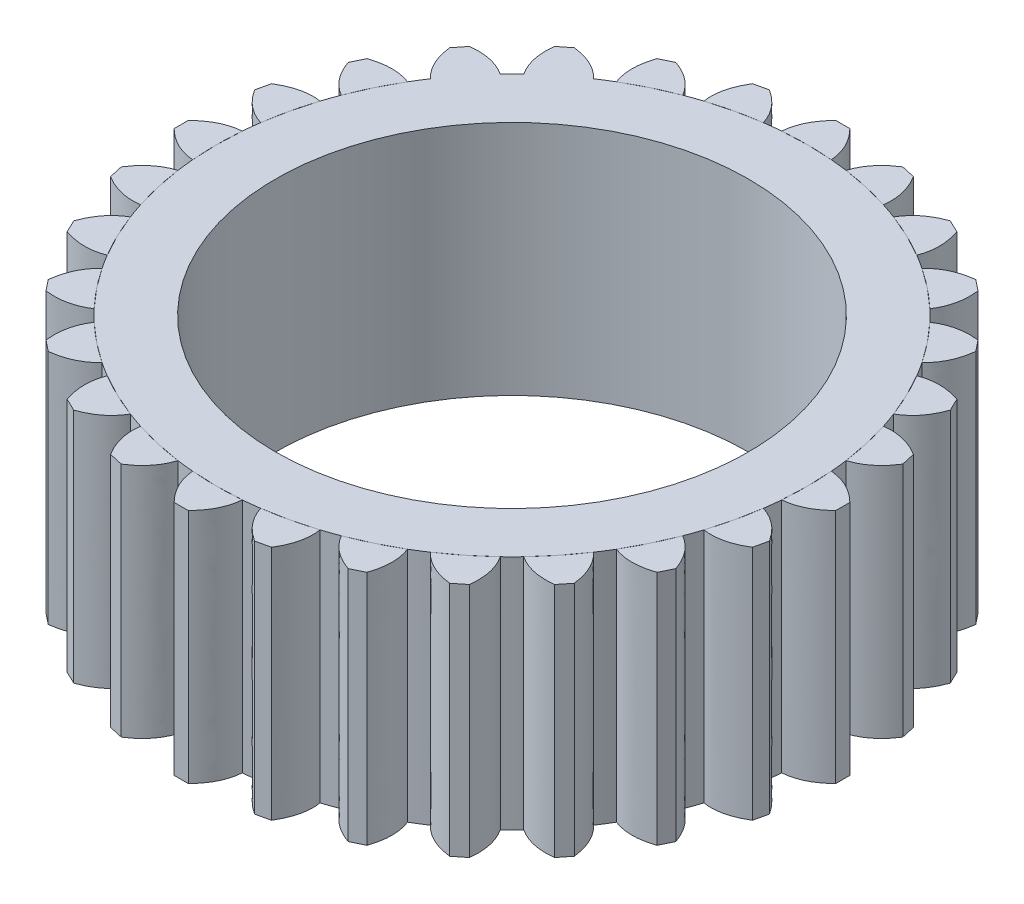
SolidWorks part; units mm, degrees
ref_plane "Front Plane" through (0, 0, 0) normal (0, 0, 1) x (1, 0, 0)
ref_plane "Top Plane" through (0, 0, 0) normal (0, 1, 0) x (1, 0, 0)
ref_plane "Right Plane" through (0, 0, 0) normal (1, 0, 0) x (0, 0, -1)
sketch "Sketch1" plane through (0, 0, 0) normal (0, 1, 0) x (1, 0, 0)
  line L0 (0, 1.4412) -> (0, -1.5503) construction
  line L1 (-0.03, 1.3989) -> (0.03, 1.3989)
  line L2 (0.105, 1.4135) -> (0.105, 1.1584) construction
  line L3 (0.282, 1.3705) -> (0.3405, 1.3572)
  line L4 (0.5799, 1.2734) -> (0.634, 1.2474)
  line L5 (0.8488, 1.1124) -> (0.8957, 1.075)
  line L6 (1.075, 0.8957) -> (1.1124, 0.8488)
  line L7 (1.2474, 0.634) -> (1.2734, 0.5799)
  line L8 (1.3572, 0.3405) -> (1.3705, 0.282)
  line L9 (1.3989, 0.03) -> (1.3989, -0.03)
  line L10 (1.3705, -0.282) -> (1.3572, -0.3405)
  line L11 (1.2734, -0.5799) -> (1.2474, -0.634)
  line L12 (1.1124, -0.8488) -> (1.075, -0.8957)
  line L13 (0.8957, -1.075) -> (0.8488, -1.1124)
  line L14 (0.634, -1.2474) -> (0.5799, -1.2734)
  line L15 (0.3405, -1.3572) -> (0.282, -1.3705)
  line L16 (0.03, -1.3989) -> (-0.03, -1.3989)
  line L17 (-0.282, -1.3705) -> (-0.3405, -1.3572)
  line L18 (-0.5799, -1.2734) -> (-0.634, -1.2474)
  line L19 (-0.8488, -1.1124) -> (-0.8957, -1.075)
  line L20 (-1.075, -0.8957) -> (-1.1124, -0.8488)
  line L21 (-1.2474, -0.634) -> (-1.2734, -0.5799)
  line L22 (-1.3572, -0.3405) -> (-1.3705, -0.282)
  line L23 (-1.3989, -0.03) -> (-1.3989, 0.03)
  line L24 (-1.3705, 0.282) -> (-1.3572, 0.3405)
  line L25 (-1.2734, 0.5799) -> (-1.2474, 0.634)
  line L26 (-1.1124, 0.8488) -> (-1.075, 0.8957)
  line L27 (-0.8957, 1.075) -> (-0.8488, 1.1124)
  line L28 (-0.634, 1.2474) -> (-0.5799, 1.2734)
  line L29 (-0.3405, 1.3572) -> (-0.282, 1.3705)
  circle A0 centre (0, 0) radius 1.25
  spline S0 degree 2 poles (0.03, 1.3989) (0.0985, 1.3294) (0.105, 1.2456) knots 0 0 0 0.82752 0.82752 0.82752
  spline S1 degree 1 poles (0, 1.25) (0.105, 1.2456) knots 0 0 1 1
  spline S2 degree 2 poles (-0.03, 1.3989) (-0.0985, 1.3294) (-0.105, 1.2456) knots 0 0 0 0.82752 0.82752 0.82752
  spline S3 degree 1 poles (0, 1.25) (-0.105, 1.2456) knots 0 0 1 1
  spline S4 degree 1 poles (0.2782, 1.2187) (0.1748, 1.2377) knots 0 0 1 1
  spline S5 degree 1 poles (0.2782, 1.2187) (0.3795, 1.191) knots 0 0 1 1
  spline S6 degree 2 poles (0.3405, 1.3572) (0.3919, 1.2742) (0.3795, 1.191) knots 0 0 0 0.82752 0.82752 0.82752
  spline S7 degree 2 poles (0.282, 1.3705) (0.1998, 1.318) (0.1748, 1.2377) knots 0 0 0 0.82752 0.82752 0.82752
  spline S8 degree 1 poles (0.5424, 1.1262) (0.4458, 1.1678) knots 0 0 1 1
  spline S9 degree 1 poles (0.5424, 1.1262) (0.635, 1.0767) knots 0 0 1 1
  spline S10 degree 2 poles (0.634, 1.2474) (0.6656, 1.155) (0.635, 1.0767) knots 0 0 0 0.82752 0.82752 0.82752
  spline S11 degree 2 poles (0.5799, 1.2734) (0.488, 1.2405) (0.4458, 1.1678) knots 0 0 0 0.82752 0.82752 0.82752
  spline S12 degree 1 poles (0.7794, 0.9773) (0.6945, 1.0393) knots 0 0 1 1
  spline S13 degree 1 poles (0.7794, 0.9773) (0.8587, 0.9084) knots 0 0 1 1
  spline S14 degree 2 poles (0.8957, 1.075) (0.9059, 0.978) (0.8587, 0.9084) knots 0 0 0 0.82752 0.82752 0.82752
  spline S15 degree 2 poles (0.8488, 1.1124) (0.7519, 1.1008) (0.6945, 1.0393) knots 0 0 0 0.82752 0.82752 0.82752
  spline S16 degree 1 poles (0.9773, 0.7794) (0.9084, 0.8587) knots 0 0 1 1
  spline S17 degree 1 poles (0.9773, 0.7794) (1.0393, 0.6945) knots 0 0 1 1
  spline S18 degree 2 poles (1.1124, 0.8488) (1.1008, 0.7519) (1.0393, 0.6945) knots 0 0 0 0.82752 0.82752 0.82752
  spline S19 degree 2 poles (1.075, 0.8957) (0.978, 0.9059) (0.9084, 0.8587) knots 0 0 0 0.82752 0.82752 0.82752
  spline S20 degree 1 poles (1.1262, 0.5424) (1.0767, 0.635) knots 0 0 1 1
  spline S21 degree 1 poles (1.1262, 0.5424) (1.1678, 0.4458) knots 0 0 1 1
  spline S22 degree 2 poles (1.2734, 0.5799) (1.2405, 0.488) (1.1678, 0.4458) knots 0 0 0 0.82752 0.82752 0.82752
  spline S23 degree 2 poles (1.2474, 0.634) (1.155, 0.6656) (1.0767, 0.635) knots 0 0 0 0.82752 0.82752 0.82752
  spline S24 degree 1 poles (1.2187, 0.2782) (1.191, 0.3795) knots 0 0 1 1
  spline S25 degree 1 poles (1.2187, 0.2782) (1.2377, 0.1748) knots 0 0 1 1
  spline S26 degree 2 poles (1.3705, 0.282) (1.318, 0.1998) (1.2377, 0.1748) knots 0 0 0 0.82752 0.82752 0.82752
  spline S27 degree 2 poles (1.3572, 0.3405) (1.2742, 0.3919) (1.191, 0.3795) knots 0 0 0 0.82752 0.82752 0.82752
  spline S28 degree 1 poles (1.25, 0) (1.2456, 0.105) knots 0 0 1 1
  spline S29 degree 1 poles (1.25, 0) (1.2456, -0.105) knots 0 0 1 1
  spline S30 degree 2 poles (1.3989, -0.03) (1.3294, -0.0985) (1.2456, -0.105) knots 0 0 0 0.82752 0.82752 0.82752
  spline S31 degree 2 poles (1.3989, 0.03) (1.3294, 0.0985) (1.2456, 0.105) knots 0 0 0 0.82752 0.82752 0.82752
  spline S32 degree 1 poles (1.2187, -0.2782) (1.2377, -0.1748) knots 0 0 1 1
  spline S33 degree 1 poles (1.2187, -0.2782) (1.191, -0.3795) knots 0 0 1 1
  spline S34 degree 2 poles (1.3572, -0.3405) (1.2742, -0.3919) (1.191, -0.3795) knots 0 0 0 0.82752 0.82752 0.82752
  spline S35 degree 2 poles (1.3705, -0.282) (1.318, -0.1998) (1.2377, -0.1748) knots 0 0 0 0.82752 0.82752 0.82752
  spline S36 degree 1 poles (1.1262, -0.5424) (1.1678, -0.4458) knots 0 0 1 1
  spline S37 degree 1 poles (1.1262, -0.5424) (1.0767, -0.635) knots 0 0 1 1
  spline S38 degree 2 poles (1.2474, -0.634) (1.155, -0.6656) (1.0767, -0.635) knots 0 0 0 0.82752 0.82752 0.82752
  spline S39 degree 2 poles (1.2734, -0.5799) (1.2405, -0.488) (1.1678, -0.4458) knots 0 0 0 0.82752 0.82752 0.82752
  spline S40 degree 1 poles (0.9773, -0.7794) (1.0393, -0.6945) knots 0 0 1 1
  spline S41 degree 1 poles (0.9773, -0.7794) (0.9084, -0.8587) knots 0 0 1 1
  spline S42 degree 2 poles (1.075, -0.8957) (0.978, -0.9059) (0.9084, -0.8587) knots 0 0 0 0.82752 0.82752 0.82752
  spline S43 degree 2 poles (1.1124, -0.8488) (1.1008, -0.7519) (1.0393, -0.6945) knots 0 0 0 0.82752 0.82752 0.82752
  spline S44 degree 1 poles (0.7794, -0.9773) (0.8587, -0.9084) knots 0 0 1 1
  spline S45 degree 1 poles (0.7794, -0.9773) (0.6945, -1.0393) knots 0 0 1 1
  spline S46 degree 2 poles (0.8488, -1.1124) (0.7519, -1.1008) (0.6945, -1.0393) knots 0 0 0 0.82752 0.82752 0.82752
  spline S47 degree 2 poles (0.8957, -1.075) (0.9059, -0.978) (0.8587, -0.9084) knots 0 0 0 0.82752 0.82752 0.82752
  spline S48 degree 1 poles (0.5424, -1.1262) (0.635, -1.0767) knots 0 0 1 1
  spline S49 degree 1 poles (0.5424, -1.1262) (0.4458, -1.1678) knots 0 0 1 1
  spline S50 degree 2 poles (0.5799, -1.2734) (0.488, -1.2405) (0.4458, -1.1678) knots 0 0 0 0.82752 0.82752 0.82752
  spline S51 degree 2 poles (0.634, -1.2474) (0.6656, -1.155) (0.635, -1.0767) knots 0 0 0 0.82752 0.82752 0.82752
  spline S52 degree 1 poles (0.2782, -1.2187) (0.3795, -1.191) knots 0 0 1 1
  spline S53 degree 1 poles (0.2782, -1.2187) (0.1748, -1.2377) knots 0 0 1 1
  spline S54 degree 2 poles (0.282, -1.3705) (0.1998, -1.318) (0.1748, -1.2377) knots 0 0 0 0.82752 0.82752 0.82752
  spline S55 degree 2 poles (0.3405, -1.3572) (0.3919, -1.2742) (0.3795, -1.191) knots 0 0 0 0.82752 0.82752 0.82752
  spline S56 degree 1 poles (0, -1.25) (0.105, -1.2456) knots 0 0 1 1
  spline S57 degree 1 poles (0, -1.25) (-0.105, -1.2456) knots 0 0 1 1
  spline S58 degree 2 poles (-0.03, -1.3989) (-0.0985, -1.3294) (-0.105, -1.2456) knots 0 0 0 0.82752 0.82752 0.82752
  spline S59 degree 2 poles (0.03, -1.3989) (0.0985, -1.3294) (0.105, -1.2456) knots 0 0 0 0.82752 0.82752 0.82752
  spline S60 degree 1 poles (-0.2782, -1.2187) (-0.1748, -1.2377) knots 0 0 1 1
  spline S61 degree 1 poles (-0.2782, -1.2187) (-0.3795, -1.191) knots 0 0 1 1
  spline S62 degree 2 poles (-0.3405, -1.3572) (-0.3919, -1.2742) (-0.3795, -1.191) knots 0 0 0 0.82752 0.82752 0.82752
  spline S63 degree 2 poles (-0.282, -1.3705) (-0.1998, -1.318) (-0.1748, -1.2377) knots 0 0 0 0.82752 0.82752 0.82752
  spline S64 degree 1 poles (-0.5424, -1.1262) (-0.4458, -1.1678) knots 0 0 1 1
  spline S65 degree 1 poles (-0.5424, -1.1262) (-0.635, -1.0767) knots 0 0 1 1
  spline S66 degree 2 poles (-0.634, -1.2474) (-0.6656, -1.155) (-0.635, -1.0767) knots 0 0 0 0.82752 0.82752 0.82752
  spline S67 degree 2 poles (-0.5799, -1.2734) (-0.488, -1.2405) (-0.4458, -1.1678) knots 0 0 0 0.82752 0.82752 0.82752
  spline S68 degree 1 poles (-0.7794, -0.9773) (-0.6945, -1.0393) knots 0 0 1 1
  spline S69 degree 1 poles (-0.7794, -0.9773) (-0.8587, -0.9084) knots 0 0 1 1
  spline S70 degree 2 poles (-0.8957, -1.075) (-0.9059, -0.978) (-0.8587, -0.9084) knots 0 0 0 0.82752 0.82752 0.82752
  spline S71 degree 2 poles (-0.8488, -1.1124) (-0.7519, -1.1008) (-0.6945, -1.0393) knots 0 0 0 0.82752 0.82752 0.82752
  spline S72 degree 1 poles (-0.9773, -0.7794) (-0.9084, -0.8587) knots 0 0 1 1
  spline S73 degree 1 poles (-0.9773, -0.7794) (-1.0393, -0.6945) knots 0 0 1 1
  spline S74 degree 2 poles (-1.1124, -0.8488) (-1.1008, -0.7519) (-1.0393, -0.6945) knots 0 0 0 0.82752 0.82752 0.82752
  spline S75 degree 2 poles (-1.075, -0.8957) (-0.978, -0.9059) (-0.9084, -0.8587) knots 0 0 0 0.82752 0.82752 0.82752
  spline S76 degree 1 poles (-1.1262, -0.5424) (-1.0767, -0.635) knots 0 0 1 1
  spline S77 degree 1 poles (-1.1262, -0.5424) (-1.1678, -0.4458) knots 0 0 1 1
  spline S78 degree 2 poles (-1.2734, -0.5799) (-1.2405, -0.488) (-1.1678, -0.4458) knots 0 0 0 0.82752 0.82752 0.82752
  spline S79 degree 2 poles (-1.2474, -0.634) (-1.155, -0.6656) (-1.0767, -0.635) knots 0 0 0 0.82752 0.82752 0.82752
  spline S80 degree 1 poles (-1.2187, -0.2782) (-1.191, -0.3795) knots 0 0 1 1
  spline S81 degree 1 poles (-1.2187, -0.2782) (-1.2377, -0.1748) knots 0 0 1 1
  spline S82 degree 2 poles (-1.3705, -0.282) (-1.318, -0.1998) (-1.2377, -0.1748) knots 0 0 0 0.82752 0.82752 0.82752
  spline S83 degree 2 poles (-1.3572, -0.3405) (-1.2742, -0.3919) (-1.191, -0.3795) knots 0 0 0 0.82752 0.82752 0.82752
  spline S84 degree 1 poles (-1.25, 0) (-1.2456, -0.105) knots 0 0 1 1
  spline S85 degree 1 poles (-1.25, 0) (-1.2456, 0.105) knots 0 0 1 1
  spline S86 degree 2 poles (-1.3989, 0.03) (-1.3294, 0.0985) (-1.2456, 0.105) knots 0 0 0 0.82752 0.82752 0.82752
  spline S87 degree 2 poles (-1.3989, -0.03) (-1.3294, -0.0985) (-1.2456, -0.105) knots 0 0 0 0.82752 0.82752 0.82752
  spline S88 degree 1 poles (-1.2187, 0.2782) (-1.2377, 0.1748) knots 0 0 1 1
  spline S89 degree 1 poles (-1.2187, 0.2782) (-1.191, 0.3795) knots 0 0 1 1
  spline S90 degree 2 poles (-1.3572, 0.3405) (-1.2742, 0.3919) (-1.191, 0.3795) knots 0 0 0 0.82752 0.82752 0.82752
  spline S91 degree 2 poles (-1.3705, 0.282) (-1.318, 0.1998) (-1.2377, 0.1748) knots 0 0 0 0.82752 0.82752 0.82752
  spline S92 degree 1 poles (-1.1262, 0.5424) (-1.1678, 0.4458) knots 0 0 1 1
  spline S93 degree 1 poles (-1.1262, 0.5424) (-1.0767, 0.635) knots 0 0 1 1
  spline S94 degree 2 poles (-1.2474, 0.634) (-1.155, 0.6656) (-1.0767, 0.635) knots 0 0 0 0.82752 0.82752 0.82752
  spline S95 degree 2 poles (-1.2734, 0.5799) (-1.2405, 0.488) (-1.1678, 0.4458) knots 0 0 0 0.82752 0.82752 0.82752
  spline S96 degree 1 poles (-0.9773, 0.7794) (-1.0393, 0.6945) knots 0 0 1 1
  spline S97 degree 1 poles (-0.9773, 0.7794) (-0.9084, 0.8587) knots 0 0 1 1
  spline S98 degree 2 poles (-1.075, 0.8957) (-0.978, 0.9059) (-0.9084, 0.8587) knots 0 0 0 0.82752 0.82752 0.82752
  spline S99 degree 2 poles (-1.1124, 0.8488) (-1.1008, 0.7519) (-1.0393, 0.6945) knots 0 0 0 0.82752 0.82752 0.82752
  spline S100 degree 1 poles (-0.7794, 0.9773) (-0.8587, 0.9084) knots 0 0 1 1
  spline S101 degree 1 poles (-0.7794, 0.9773) (-0.6945, 1.0393) knots 0 0 1 1
  spline S102 degree 2 poles (-0.8488, 1.1124) (-0.7519, 1.1008) (-0.6945, 1.0393) knots 0 0 0 0.82752 0.82752 0.82752
  spline S103 degree 2 poles (-0.8957, 1.075) (-0.9059, 0.978) (-0.8587, 0.9084) knots 0 0 0 0.82752 0.82752 0.82752
  spline S104 degree 1 poles (-0.5424, 1.1262) (-0.635, 1.0767) knots 0 0 1 1
  spline S105 degree 1 poles (-0.5424, 1.1262) (-0.4458, 1.1678) knots 0 0 1 1
  spline S106 degree 2 poles (-0.5799, 1.2734) (-0.488, 1.2405) (-0.4458, 1.1678) knots 0 0 0 0.82752 0.82752 0.82752
  spline S107 degree 2 poles (-0.634, 1.2474) (-0.6656, 1.155) (-0.635, 1.0767) knots 0 0 0 0.82752 0.82752 0.82752
  spline S108 degree 1 poles (-0.2782, 1.2187) (-0.3795, 1.191) knots 0 0 1 1
  spline S109 degree 1 poles (-0.2782, 1.2187) (-0.1748, 1.2377) knots 0 0 1 1
  spline S110 degree 2 poles (-0.282, 1.3705) (-0.1998, 1.318) (-0.1748, 1.2377) knots 0 0 0 0.82752 0.82752 0.82752
  spline S111 degree 2 poles (-0.3405, 1.3572) (-0.3919, 1.2742) (-0.3795, 1.191) knots 0 0 0 0.82752 0.82752 0.82752
  point P12 (0, 1.3989)
  dimension "D1" = 2.5
  dimension "D2" = 0.03
  dimension "D3" = 0.105
  dimension "D4" = 28
extrude "Boss-Extrude1" add sketch "Sketch1" against normal blind 1 contours S109 S108 A0 S105 S104 S101 S100 S97 S96 S93 S92 S89 S88 S85 S84 S81 S80 S77 S76 S73 S72 S69 S68 S65 S64 S61 S60 S57 S56 S53 S52 S49 S48 S45 S44 | L13 S47 A0 S46 | L12 S43 A0 S42 | L11 S39 A0 S38 | L10 S35 A0 S34 | L9 S31 A0 S30 | L8 S27 A0 S26 | L7 S23 A0 S22 | L6 S19 A0 S18 | L5 S15 A0 S14 | L4 S11 A0 S10 | L3 S7 A0 S6 | L1 S2 A0 S0 | L29 S111 A0 S110 | L28 S107 A0 S106 | L25 S95 A0 S94 | L24 S91 A0 S90 | L23 S87 A0 S86 | L22 S83 A0 S82 | L21 S79 A0 S78 | L20 S75 A0 S74 | L19 S71 A0 S70 | L18 S67 A0 S66 | L17 S63 A0 S62 | L16 S59 A0 S58 | L15 S55 A0 S54 | L14 S51 A0 S50
sketch "Sketch2" plane through (0, 0, 0) normal (0, 1, 0) x (1, 0, 0)
  circle A0 centre (0, 0) radius 1
  dimension "D1" = 2
extrude "Cut-Extrude1" cut sketch "Sketch2" against normal blind 1
